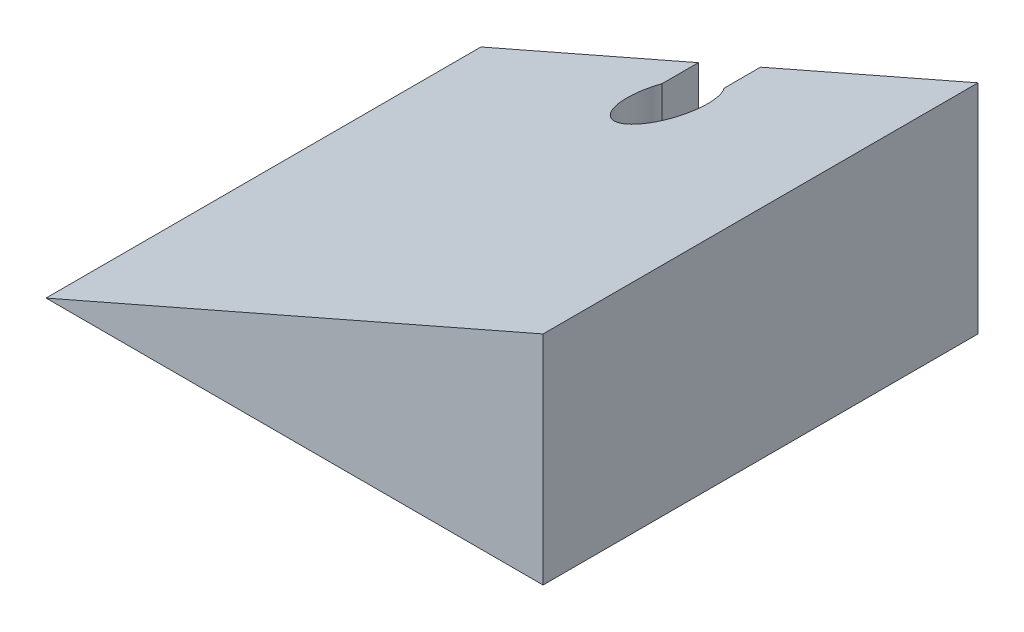
SolidWorks part; units mm, degrees
ref_plane "Front Plane" through (0, 0, 0) normal (0, 0, 1) x (1, 0, 0)
ref_plane "Top Plane" through (0, 0, 0) normal (0, 1, 0) x (1, 0, 0)
ref_plane "Right Plane" through (0, 0, 0) normal (1, 0, 0) x (0, 0, -1)
sketch "Esboço1" plane through (0, 0, 0) normal (0, 0, 1) x (1, 0, 0)
  line L0 (-46.1667, -15.6528) -> (33.8333, 19.3472)
  line L3 (-46.1667, -15.6528) -> (33.8333, -15.6528)
  line L4 (33.8333, 19.3472) -> (33.8333, -15.6528)
  dimension "D1" = 35
  dimension "D2" = 80
extrude "Ressalto-extrusão1" add sketch "Esboço1" along normal blind 70
sketch "Esboço2" plane through (0, -15.6528, 0) normal (0, -1, 0) x (1, 0, 0)
  line L0 (33.8333, 35) -> (-46.1667, 35) construction
  line L1 (33.8333, 70) -> (33.8333, 0) construction
  line L2 (-46.1667, 70) -> (-46.1667, 0) construction
  line L3 (-6.1667, 0) -> (-6.1667, 3.5) construction
  line L4 (-46.1667, 0) -> (33.8333, 0) construction
  line L5 (-46.1667, 70) -> (33.8333, 70) construction
  line L6 (-6.1667, 10) -> (-6.1667, 70) construction
  line L7 (-11.1667, 0) -> (-1.1667, 0)
  line L8 (-11.1667, 0) -> (-11.1667, 5.8467)
  line L10 (-1.1667, 0) -> (-1.1667, 5.8467)
  arc A0 (-1.1667, 5.8467) -> (-11.1667, 5.8467) centre (-6.1667, 10) ccw
  point P16 (-6.1667, 0)
  point P19 (0, 0)
  dimension "D3" = 13
  dimension "D1" = 5
extrude "Corte-extrusão1" cut sketch "Esboço2" against normal blind 70
